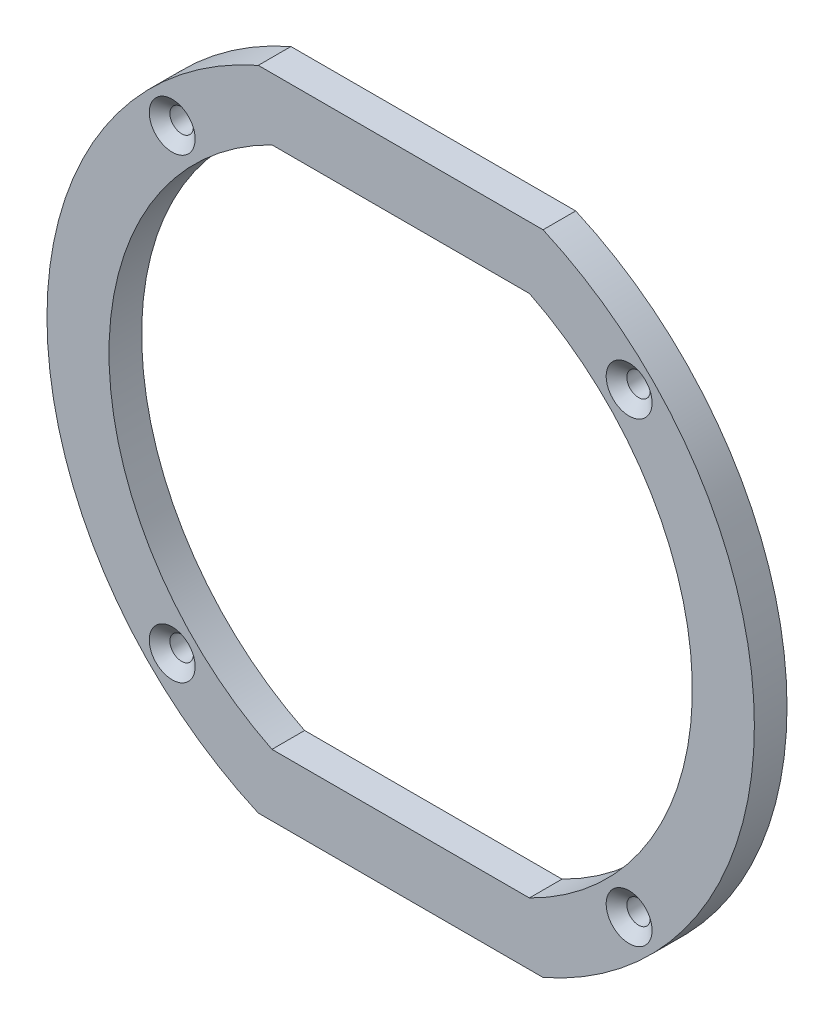
SolidWorks part; units mm, degrees
material "1060 Alloy"
ref_plane "Front Plane" through (0, 0, 0) normal (0, 0, 1) x (1, 0, 0)
ref_plane "Top Plane" through (0, 0, 0) normal (0, 1, 0) x (1, 0, 0)
ref_plane "Right Plane" through (0, 0, 0) normal (1, 0, 0) x (0, 0, -1)
sketch "Sketch1" plane through (0, 0, 0) normal (0, 0, 1) x (1, 0, 0)
  line L0 (0, -48.1) -> (0, 48.1) construction
  line L1 (-23.6506, 48.1) -> (23.6506, 48.1)
  line L2 (-23.6506, -48.1) -> (23.6506, -48.1)
  line L3 (0, -59.5) -> (0, 59.5) construction
  line L4 (-26.1677, 59.5) -> (26.1677, 59.5)
  line L5 (-26.1677, -59.5) -> (26.1677, -59.5)
  arc A0 (-26.1677, 59.5) -> (-26.1677, -59.5) centre (0, 0) ccw
  arc A1 (-23.6506, 48.1) -> (-23.6506, -48.1) centre (0, 0) ccw
  arc A2 (23.6506, -48.1) -> (23.6506, 48.1) centre (0, 0) ccw
  arc A3 (26.1677, -59.5) -> (26.1677, 59.5) centre (0, 0) ccw
  point P6 (0, 0)
  point P9 (0, 48.1)
  point P13 (0, -48.1)
  point P15 (0, 0)
  point P17 (0, 59.5)
  point P20 (0, -59.5)
  dimension "D1" = 130
  dimension "D2" = 107.2
  dimension "D3" = 96.2
  dimension "D4" = 119
extrude "Boss-Extrude1" add sketch "Sketch1" along normal blind 6
hole_wizard "CSK for #8 Flat Head Machine Screw (100)1" positions "Sketch2" profile "Sketch4" countersink size "#8" standard "ANSI Inch" end condition through all
sketch "Sketch2" plane through (0, 0, 6) normal (0, 0, 1) x (1, 0, 0)
  line L1 (-41.985, -41.985) -> (41.985, -41.985) construction
  line L2 (-41.985, -41.985) -> (-41.985, 41.985) construction
  line L3 (-41.985, 41.985) -> (41.985, 41.985) construction
  line L4 (41.985, -41.985) -> (41.985, 41.985) construction
  line L5 (-41.985, -41.985) -> (41.985, 41.985) construction
  line L6 (-41.985, 41.985) -> (41.985, -41.985) construction
  point P1 (0, 0)
  point P2 (41.985, 41.985)
  point P39 (-41.985, -41.985)
  point P40 (-41.985, 41.985)
  point P41 (41.985, -41.985)
  dimension "D1" = 83.97
sketch "Sketch4" plane through (0, 0, 6) normal (1, 0, 0) x (0, -1, 0)
  line L0 (0, 0) -> (0, 6)
  line L1 (0, 6) -> (2.1526, 6)
  line L2 (2.1526, 6) -> (2.1526, 1.7317)
  line L3 (2.1526, 1.7317) -> (4.2164, 0)
  line L5 (4.2164, 0) -> (0, 0)
  line L6 (-2.1526, 1.7317) -> (-4.2164, 0) construction
  line L11 (0, -6.35) -> (0, 107.95) construction
  dimension "Thru Hole Dia." = 4.3053
  dimension "Thru Hole Depth" = 6
  dimension "Near C'Sink Dia." = 8.4328
  dimension "Near C'Sink Angle" = 100
sketch "Sketch5" plane through (0, 0, 0) normal (0, 0, -1) x (-1, 0, 0)
  line L0 (59.2455, 0) -> (-59.2455, 0) construction
  circle A0 centre (-59.2455, 0) radius 1.905
  circle A1 centre (59.2455, 0) radius 1.905
  point P4 (0, 0)
  dimension "D2" = 3.81
  dimension "D1" = 118.491
extrude "Boss-Extrude2" add sketch "Sketch5" along normal blind 2.5
